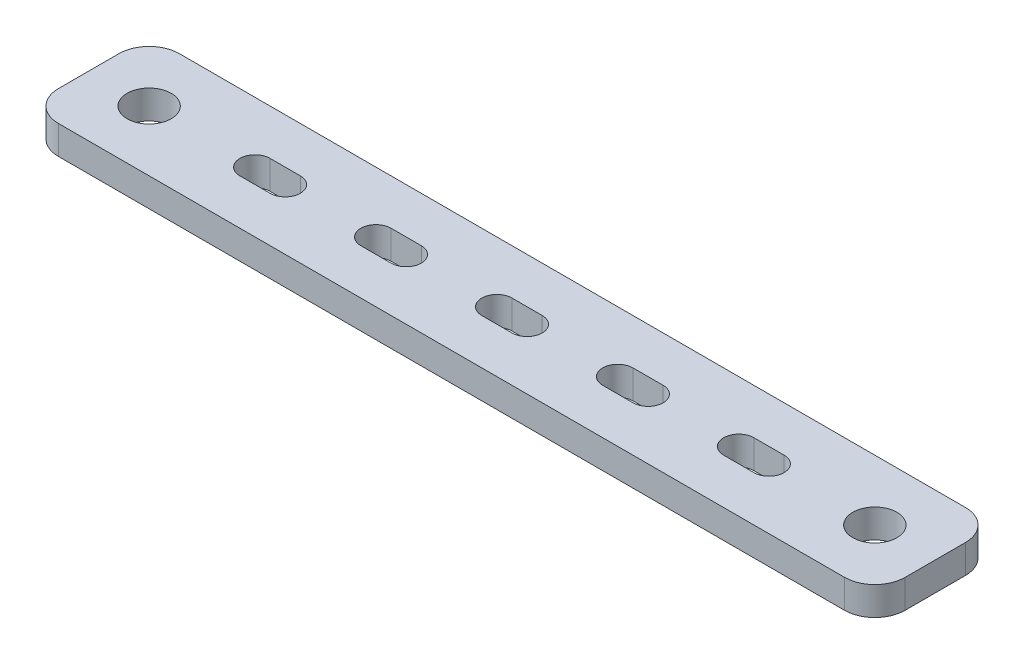
SolidWorks part; units mm, degrees
ref_plane "Front" through (0, 0, 0) normal (0, 0, 1) x (1, 0, 0)
ref_plane "Top" through (0, 0, 0) normal (0, 1, 0) x (1, 0, 0)
ref_plane "Right" through (0, 0, 0) normal (1, 0, 0) x (0, 0, -1)
sketch "Sketch1" plane through (0, 0, 0) normal (0, 1, 0) x (1, 0, 0)
  line L1 (88.9, -12.7) -> (-88.9, -12.7)
  line L2 (88.9, -12.7) -> (88.9, 12.7)
  line L3 (88.9, 12.7) -> (-88.9, 12.7)
  line L4 (-88.9, -12.7) -> (-88.9, 12.7)
  line L5 (88.9, -12.7) -> (-88.9, 12.7) construction
  line L6 (88.9, 12.7) -> (-88.9, -12.7) construction
  point P0 (0, 0)
  dimension "D1" = 25.4
  dimension "D2" = 177.8
extrude "Boss-Extrude1" add sketch "Sketch1" along normal blind 6
sketch "Sketch4" plane through (0, 0, 0) normal (0, -1, 0) x (1, 0, 0)
  line L0 (-76.2, 0) -> (76.2, 0) construction
  line L1 (-53.975, 0) -> (-47.625, 0) construction
  line L2 (-53.975, 3.175) -> (-47.625, 3.175)
  line L3 (-53.975, -3.175) -> (-47.625, -3.175)
  line L4 (-28.575, 0) -> (-22.225, 0) construction
  line L5 (-28.575, 3.175) -> (-22.225, 3.175)
  line L6 (-28.575, -3.175) -> (-22.225, -3.175)
  line L7 (-3.175, 0) -> (3.175, 0) construction
  line L8 (-3.175, 3.175) -> (3.175, 3.175)
  line L9 (-3.175, -3.175) -> (3.175, -3.175)
  line L10 (22.225, 0) -> (28.575, 0) construction
  line L11 (22.225, 3.175) -> (28.575, 3.175)
  line L12 (22.225, -3.175) -> (28.575, -3.175)
  line L13 (47.625, 0) -> (53.975, 0) construction
  line L14 (47.625, 3.175) -> (53.975, 3.175)
  line L15 (47.625, -3.175) -> (53.975, -3.175)
  arc A0 (-53.975, 3.175) -> (-53.975, -3.175) centre (-53.975, 0) ccw
  arc A1 (-47.625, -3.175) -> (-47.625, 3.175) centre (-47.625, 0) ccw
  arc A2 (-28.575, 3.175) -> (-28.575, -3.175) centre (-28.575, 0) ccw
  arc A3 (-22.225, -3.175) -> (-22.225, 3.175) centre (-22.225, 0) ccw
  arc A4 (-3.175, 3.175) -> (-3.175, -3.175) centre (-3.175, 0) ccw
  arc A5 (3.175, -3.175) -> (3.175, 3.175) centre (3.175, 0) ccw
  arc A6 (22.225, 3.175) -> (22.225, -3.175) centre (22.225, 0) ccw
  arc A7 (28.575, -3.175) -> (28.575, 3.175) centre (28.575, 0) ccw
  arc A8 (47.625, 3.175) -> (47.625, -3.175) centre (47.625, 0) ccw
  arc A9 (53.975, -3.175) -> (53.975, 3.175) centre (53.975, 0) ccw
  point P6 (-50.8, 0)
  point P14 (-25.4, 0)
  point P21 (0, 0)
  point P28 (25.4, 0)
  point P35 (50.8, 0)
  dimension "D1" = 6.35
  dimension "D2" = 6.35
  dimension "D3" = 25.4
  dimension "D4" = 5
extrude "Cut-Extrude2" cut sketch "Sketch4" against normal through all
fillet "Fillet1" radius 6.35 4 edges at (88.9, 3, 12.7) (88.9, 3, -12.7) (-88.9, 3, 12.7) (-88.9, 3, -12.7)
sketch "Sketch5" plane through (0, 6, 0) normal (0, 1, 0) x (1, 0, 0)
  line L0 (-76.2, 0) -> (0, 0) construction
  circle A0 centre (-76.2, 0) radius 4.6355
  dimension "D1" = 76.2
  dimension "D2" = 9.271
extrude "Cut-Extrude3" cut sketch "Sketch5" against normal through all
mirror "Mirror1" about plane through (0, 0, 0) normal (1, 0, 0) of "Cut-Extrude3"
sketch "Sketch6" [suppressed] plane through (0, 5.842, 0) normal (0, 1, 0) x (1, 0, 0)
  line L0 (0, 0) -> (76.2, 0) construction
  circle A0 centre (76.2, 0) radius 6.35
  dimension "D2" = 12.7
  dimension "D1" = 76.2
extrude "Cut-Extrude4" [suppressed] cut sketch "Sketch6" against normal through all
hole_wizard "#6 Clearance Hole1" [suppressed] positions "Sketch8" profile "Sketch9" hole size "#6" standard "ANSI Inch"
sketch "Sketch8" plane through (0, 5.842, 0) normal (0, 1, 0) x (1, 0, 0)
  line L1 (69.2852, -6.9148) -> (83.1148, -6.9148) construction
  line L2 (69.2852, -6.9148) -> (69.2852, 6.9148) construction
  line L3 (69.2852, 6.9148) -> (83.1148, 6.9148) construction
  line L4 (83.1148, -6.9148) -> (83.1148, 6.9148) construction
  line L5 (69.2852, -6.9148) -> (83.1148, 6.9148) construction
  line L6 (69.2852, 6.9148) -> (83.1148, -6.9148) construction
  point P1 (76.2, 0)
  point P124 (69.2852, 6.9148)
  dimension "D1" = 19.558
sketch "Sketch9" plane through (76.2, 5.842, 0) normal (1, 0, 0) x (0, 0, 1)
  line L0 (0, 0) -> (0, 10.4511)
  line L1 (0, 10.4511) -> (1.7526, 9.398)
  line L2 (1.7526, 9.398) -> (1.7526, 0)
  line L5 (1.7526, 0) -> (0, 0)
  line L10 (0, 10.4511) -> (-1.7526, 9.398) construction
  line L11 (0, -6.35) -> (0, 107.95) construction
  dimension "Hole Dia." = 3.5052
  dimension "Hole Depth" = 9.398
  dimension "Drill Angle" = 118
pattern_circular "CirPattern1" [suppressed] count 4 over 360
